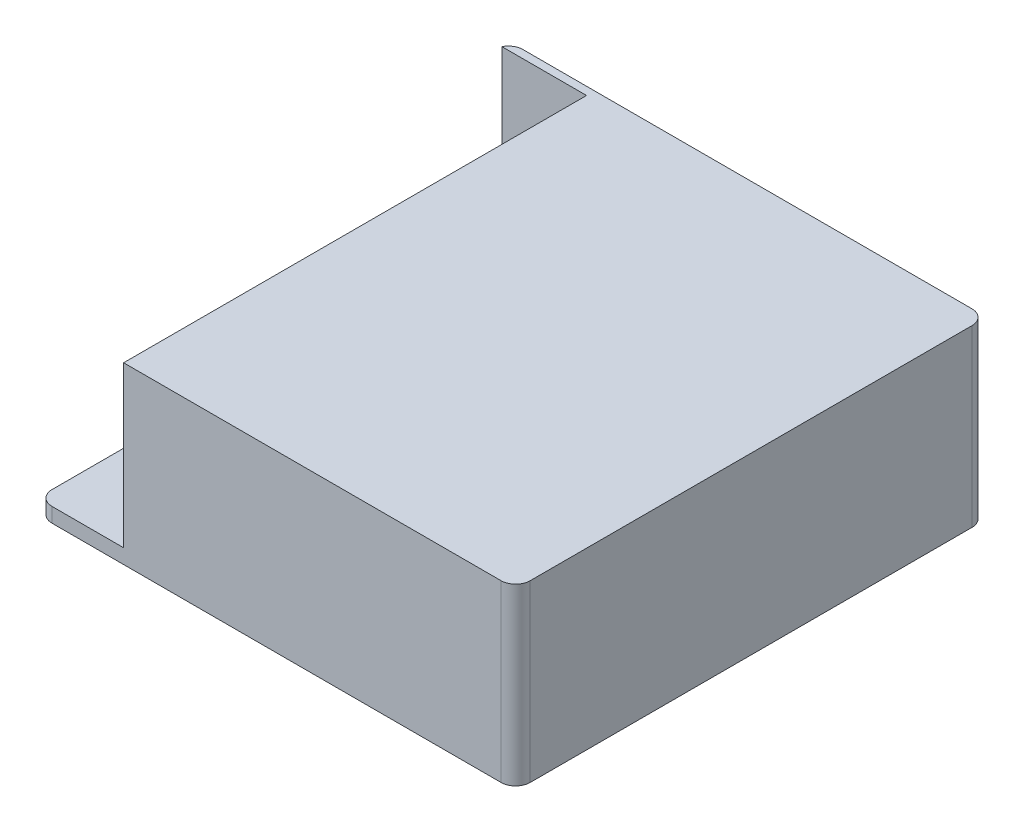
SolidWorks part; units mm, degrees
ref_plane "Front Plane" through (0, 0, 0) normal (0, 0, 1) x (1, 0, 0)
ref_plane "Top Plane" through (0, 0, 0) normal (0, 1, 0) x (1, 0, 0)
ref_plane "Right Plane" through (0, 0, 0) normal (1, 0, 0) x (0, 0, -1)
sketch "Sketch1" plane through (0, 0, 0) normal (0, 1, 0) x (1, 0, 0)
  line L1 (-46.25, 48.5) -> (46.25, 48.5)
  line L2 (-49.25, 45.5) -> (-49.25, -45.5)
  line L3 (-46.25, -48.5) -> (46.25, -48.5)
  line L4 (49.25, 45.5) -> (49.25, -45.5)
  line L5 (-49.25, 48.5) -> (49.25, -48.5) construction
  line L6 (-49.25, -48.5) -> (49.25, 48.5) construction
  arc A0 (49.25, -45.5) -> (46.25, -48.5) centre (46.25, -45.5) cw
  arc A1 (49.25, 45.5) -> (46.25, 48.5) centre (46.25, 45.5) ccw
  arc A2 (-49.25, 45.5) -> (-46.25, 48.5) centre (-46.25, 45.5) cw
  arc A3 (-49.25, -45.5) -> (-46.25, -48.5) centre (-46.25, -45.5) ccw
  point P0 (0, 0)
  dimension "D1" = 3
extrude "Boss-Extrude1" add sketch "Sketch1" along normal blind 36
sketch "Sketch2" plane through (0, 36, 0) normal (0, 1, 0) x (1, 0, 0)
  line L1 (-56.5894, 46.8529) -> (-31.4967, 46.8529)
  line L2 (-56.5894, 46.8529) -> (-56.5894, -51.1657)
  line L3 (-56.5894, -51.1657) -> (-31.4967, -51.1657)
  line L4 (-31.4967, 46.8529) -> (-31.4967, -51.1657)
extrude "Cut-Extrude1" cut sketch "Sketch2" against normal blind 33
sketch "Sketch3" plane through (0, 3, 0) normal (0, 1, 0) x (1, 0, 0)
  line L0 (-49.25, 45.5) -> (-49.25, -45.5) construction
  line L1 (-49.25, 37.7045) -> (-31.4967, 37.7045)
  line L2 (-49.25, 37.7045) -> (-49.25, -20.5839)
  line L3 (-49.25, -20.5839) -> (-31.4967, -20.5839)
  line L4 (-31.4967, 37.7045) -> (-31.4967, -20.5839)
  line L5 (-31.4967, 46.8529) -> (-31.4967, -48.5) construction
extrude "Boss-Extrude2" add sketch "Sketch3" along normal blind 12 separate body
